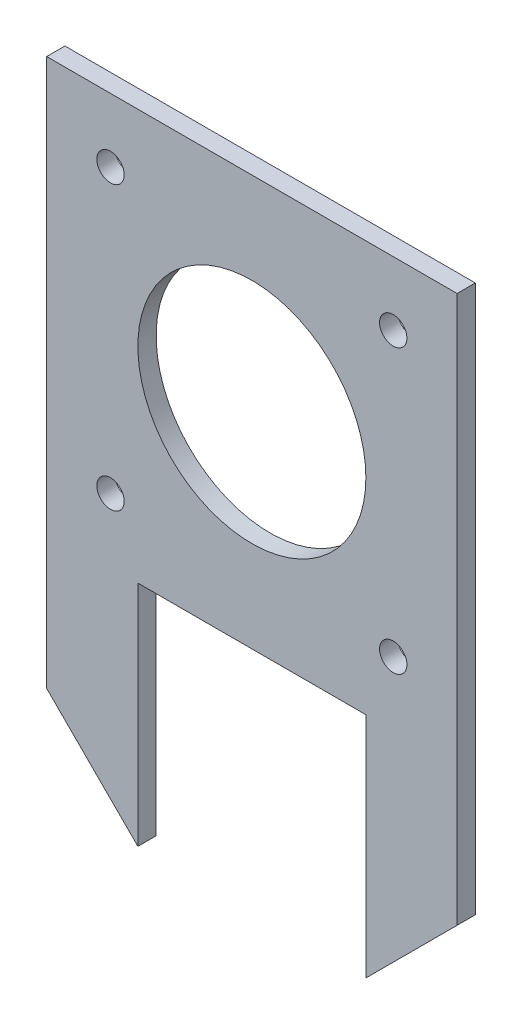
SolidWorks part; units mm, degrees
ref_plane "Plan de face" through (0, 0, 0) normal (0, 0, 1) x (1, 0, 0)
ref_plane "Plan de dessus" through (0, 0, 0) normal (0, 1, 0) x (1, 0, 0)
ref_plane "Plan de droite" through (0, 0, 0) normal (1, 0, 0) x (0, 0, -1)
sketch "Esquisse1" plane through (0, 0, 0) normal (0, 0, 1) x (1, 0, 0)
  line L0 (-35, 70) -> (10, 70)
  line L2 (0, 0) -> (0, 25)
  line L3 (0, 25) -> (-25, 25)
  line L4 (-25, 0) -> (-25, 25)
  line L5 (10, 70) -> (10, 10)
  line L6 (10, 10) -> (0, 0)
  line L7 (0, 0) -> (0.2996, -0.7798)
  line L8 (-25, 0) -> (-35, 10)
  line L9 (-35, 10) -> (-35, 70)
  circle A0 centre (-12.5, 47.5) radius 12.5
  circle A1 centre (-28, 63) radius 1.5
  circle A2 centre (3, 63) radius 1.5
  circle A3 centre (3, 32) radius 1.5
  circle A4 centre (-28, 32) radius 1.5
  dimension "D8" = 25
  dimension "D10" = 3
  dimension "D11" = 3
  dimension "D12" = 3
  dimension "D13" = 3
  dimension "D1" = 25
  dimension "D2" = 45
  dimension "D3" = 10
  dimension "D4" = 45
  dimension "D5" = 25
  dimension "D6" = 45
  dimension "D7" = 22.5
  dimension "D9" = 22.5
  dimension "D14" = 31
  dimension "D15" = 31
  dimension "D16" = 31
  dimension "D17" = 31
  dimension "D18" = 7
  dimension "D19" = 7
  dimension "D20" = 7
  dimension "D21" = 45
  dimension "D22" = 7
extrude "Boss.-Extru.1" add sketch "Esquisse1" along normal blind 2 contours L9 L8 L4 L3 L2 L6 L5 L0 A4 A3 A2 A1 A0
